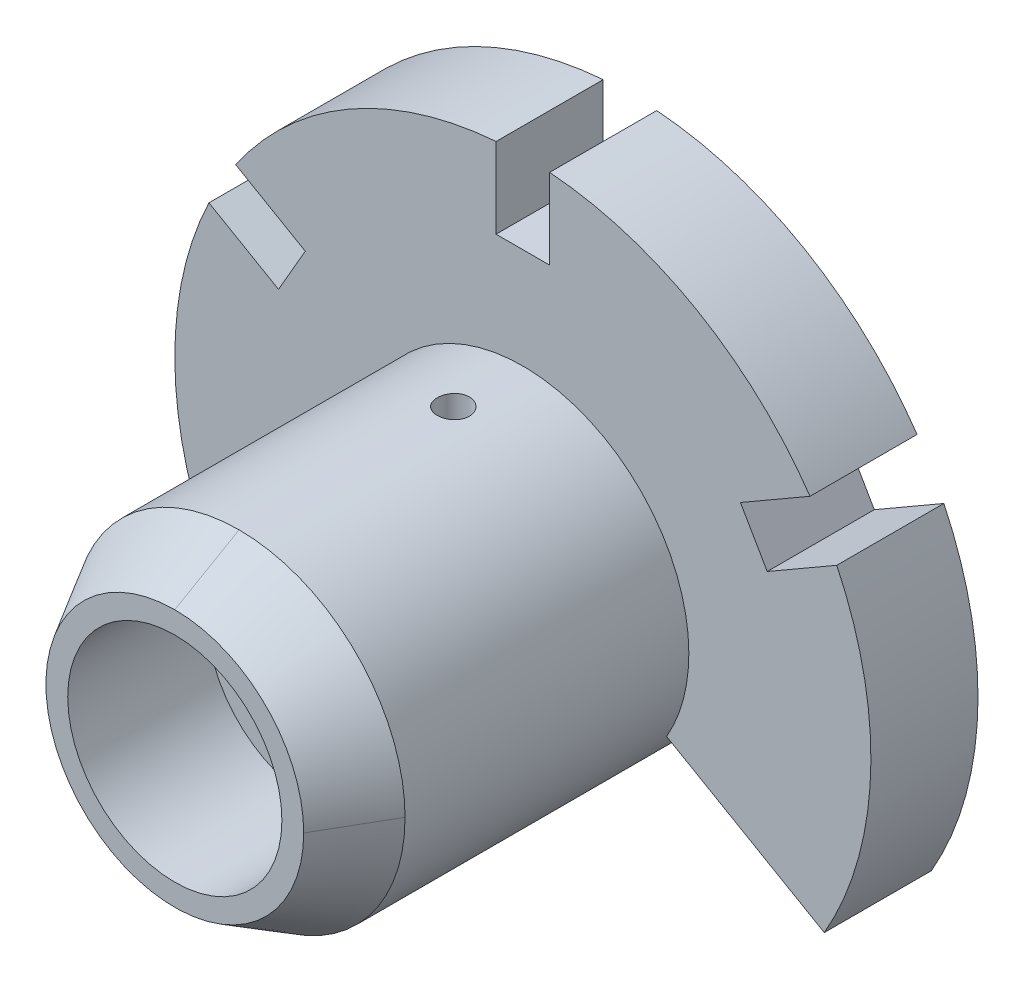
SolidWorks part; units mm, degrees
ref_plane "Front Plane" through (0, 0, 0) normal (0, 0, 1) x (1, 0, 0)
ref_plane "Top Plane" through (0, 0, 0) normal (0, 1, 0) x (1, 0, 0)
ref_plane "Right Plane" through (0, 0, 0) normal (1, 0, 0) x (0, 0, -1)
sketch "Sketch2" plane through (0, 0, 0) normal (0, 0, 1) x (1, 0, 0)
  line L0 (0, 49.8074) -> (0, 0) construction
  line L2 (-5, 64.8074) -> (-5, 49.8074)
  line L3 (-5, 49.8074) -> (5, 49.8074)
  line L4 (5, 49.8074) -> (5, 64.8074)
  line L5 (40.6345, 29.2338) -> (45.6345, 20.5736)
  line L6 (53.6249, 36.7338) -> (40.6345, 29.2338)
  line L7 (45.6345, 20.5736) -> (58.6249, 28.0736)
  line L17 (-45.6345, 20.5736) -> (-40.6345, 29.2338)
  line L18 (-58.6249, 28.0736) -> (-45.6345, 20.5736)
  line L19 (-40.6345, 29.2338) -> (-53.6249, 36.7338)
  line L20 (-45.6345, -20.5736) -> (-58.6249, -28.0736) [skipped]
  line L21 (-53.6249, -36.7338) -> (-40.6345, -29.2338) [skipped]
  line L22 (-40.6345, -29.2338) -> (-45.6345, -20.5736) [skipped]
  line L23 (-5, -49.8074) -> (-5, -64.8074) [skipped]
  line L24 (5, -64.8074) -> (5, -49.8074) [skipped]
  line L25 (45.6345, -20.5736) -> (40.6345, -29.2338) [skipped]
  line L26 (58.6249, -28.0736) -> (45.6345, -20.5736) [skipped]
  line L27 (40.6345, -29.2338) -> (53.6249, -36.7338) [skipped]
  line L28 (5, -49.8074) -> (-5, -49.8074) [skipped]
  line L29 (0, 0) -> (-43.1345, 24.9037) construction
  line L30 (0, 0) -> (-56.2917, -32.5)
  line L31 (0, 0) -> (56.2917, -32.5)
  arc A0 (-5, 64.8074) -> (-53.6249, 36.7338) centre (0, 0) ccw
  arc A1 (53.6249, 36.7338) -> (5, 64.8074) centre (0, 0) ccw
  arc A6 (-5, 64.8074) -> (-53.6249, 36.7338) centre (0, 0) ccw
  arc A7 (-5, 64.8074) -> (-53.6249, 36.7338) centre (0, 0) ccw
  arc A8 (-58.6249, 28.0736) -> (-56.2917, -32.5) centre (0, 0) ccw
  arc A9 (-58.6249, 28.0736) -> (-56.2917, -32.5) centre (0, 0) ccw
  arc A10 (-58.6249, 28.0736) -> (-58.6249, -28.0736) centre (0, 0) ccw
  arc A11 (53.6249, 36.7338) -> (5, 64.8074) centre (0, 0) ccw
  arc A12 (53.6249, 36.7338) -> (5, 64.8074) centre (0, 0) ccw
  arc A13 (53.6249, 36.7338) -> (5, 64.8074) centre (0, 0) ccw
  arc A14 (53.6249, 36.7338) -> (5, 64.8074) centre (0, 0) ccw
  arc A15 (53.6249, 36.7338) -> (5, 64.8074) centre (0, 0) ccw
  arc A16 (-43.6661, -48.1484) -> (58.6249, 28.0736) centre (0, 0) ccw [skipped]
  arc A17 (-30.1748, -57.5715) -> (58.6249, 28.0736) centre (0, 0) ccw [skipped]
  arc A18 (5, -64.8074) -> (58.6249, 28.0736) centre (0, 0) ccw [skipped]
  arc A19 (58.6249, -28.0736) -> (58.6249, 28.0736) centre (0, 0) ccw [skipped]
  arc A20 (-5, 64.8074) -> (-53.6249, 36.7338) centre (0, 0) ccw
  arc A21 (-5, 64.8074) -> (-53.6249, 36.7338) centre (0, 0) ccw
  arc A22 (-5, 64.8074) -> (-53.6249, 36.7338) centre (0, 0) ccw
  arc A23 (56.2917, -32.5) -> (58.6249, 28.0736) centre (0, 0) ccw
  arc A24 (56.2917, -32.5) -> (58.6249, 28.0736) centre (0, 0) ccw
  point P7 (0, 64.8074)
  point P31 (0, 0)
  dimension "D1" = 130
  dimension "D2" = 10
  dimension "D3" = 15
  dimension "D5" = 60
  dimension "D6" = 60
  dimension "D4" = 6
extrude "Boss-Extrude1" add sketch "Sketch2" along normal blind 20 contours L31 A23 L7 L5 L6 A1 L4 L3 L2 A0 L19 L17 L18 A8 A9 L30
sketch "Sketch3" plane through (0, 0, 20) normal (0, 0, 1) x (1, 0, 0)
  circle A0 centre (0, 0) radius 12.5
  circle A1 centre (0, 0) radius 31
  dimension "D1" = 25
  dimension "D2" = 62
extrude "Boss-Extrude2" add sketch "Sketch3" along normal blind 65 and the other way blind 20
sketch "Sketch4" plane through (0, 0, 85) normal (0, 0, 1) x (1, 0, 0)
  circle A1 centre (0, 0) radius 31
  circle A2 centre (0, 0) radius 31 construction
  dimension "D1" = 0
sketch "Sketch5" plane through (0, 0, 0) normal (1, 0, 0) x (0, 0, -1)
  line L0 (-85, 31) -> (-73, 31)
  line L1 (-20, 31) -> (-85, 31) construction
  line L2 (-73, 31) -> (-85, 24.0718)
  line L3 (-85, 31) -> (-85, -31) construction
  line L4 (-85, 24.0718) -> (-85, 31)
  point P5 (-85, 27.5359)
  dimension "D1" = 12
  dimension "D2" = 30
sweep "Cut-Sweep1" cut profiles "Sketch5" path edge at (31, 0, 85)
sketch "Sketch6" plane through (0, 0, 85) normal (0, 0, 1) x (1, 0, 0)
  circle A0 centre (0, 0) radius 20
  dimension "D1" = 40
extrude "Cut-Extrude1" cut sketch "Sketch6" against normal blind 26
sketch "Sketch8" plane through (0, 0, 20) normal (0, 0, 1) x (1, 0, 0)
  circle A0 centre (0, 0) radius 12.5 construction
  circle A1 centre (0, 0) radius 12.5
extrude "Cut-Extrude2" cut sketch "Sketch8" against normal blind 20
sketch "Sketch9" plane through (0, 0, 0) normal (0, 1, 0) x (1, 0, 0)
  line L0 (-31, -85) -> (31, -85) construction
  line L1 (0, 0) -> (0, -33) construction
  circle A0 centre (0, -33) radius 3
  dimension "D1" = 6
  dimension "D2" = 52
extrude "Cut-Extrude3" cut sketch "Sketch9" along normal blind 33
